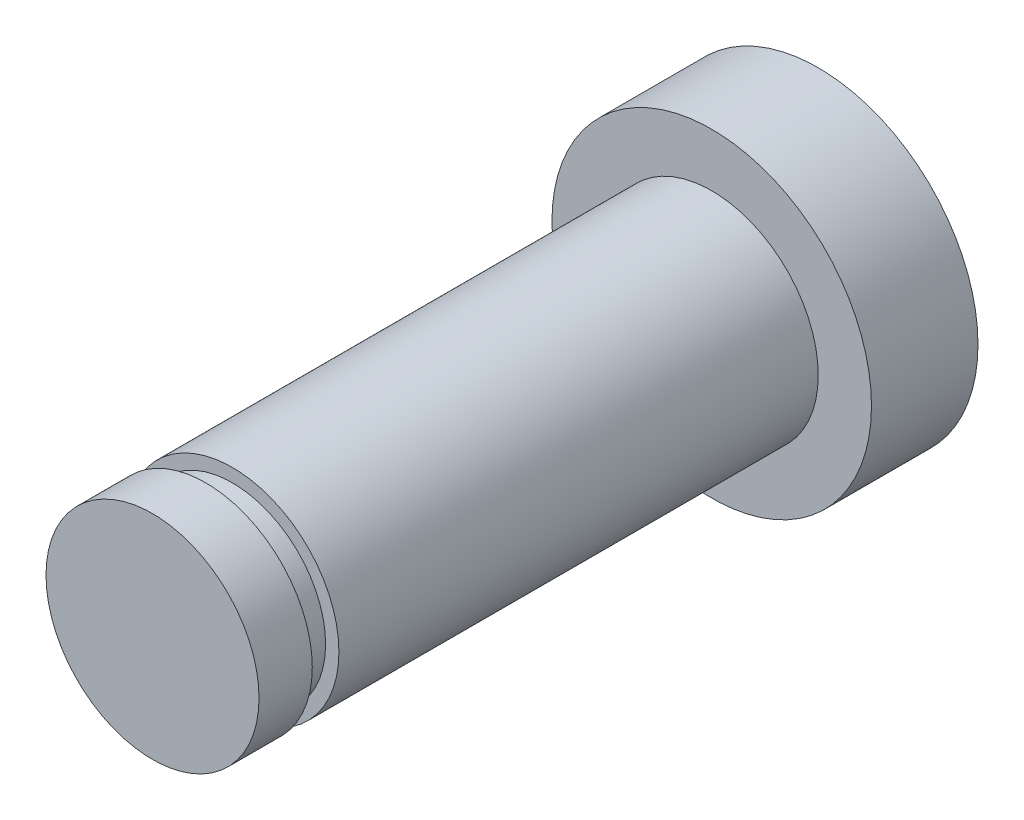
SolidWorks part; units mm, degrees
material "6061 合金"
ref_plane "前视基准面" through (0, 0, 0) normal (0, 0, 1) x (1, 0, 0)
ref_plane "上视基准面" through (0, 0, 0) normal (0, 1, 0) x (1, 0, 0)
ref_plane "右视基准面" through (0, 0, 0) normal (1, 0, 0) x (0, 0, -1)
sketch "草图1" plane through (0, 0, 0) normal (0, 0, 1) x (1, 0, 0)
  circle A0 centre (0, 0) radius 6
extrude "凸台-拉伸1" add sketch "草图1" along normal blind 4
sketch "草图2" plane through (0, 0, 4) normal (0, 0, 1) x (1, 0, 0)
  circle A0 centre (0, 0) radius 4
extrude "凸台-拉伸2" add sketch "草图2" along normal blind 18
sketch "草图3" plane through (0, 0, 22) normal (0, 0, 1) x (1, 0, 0)
  circle A0 centre (0, 0) radius 3.5
extrude "凸台-拉伸3" add sketch "草图3" along normal blind 1
sketch "草图4" plane through (0, 0, 23) normal (0, 0, 1) x (1, 0, 0)
  circle A0 centre (0, 0) radius 4
extrude "凸台-拉伸4" add sketch "草图4" along normal blind 2
